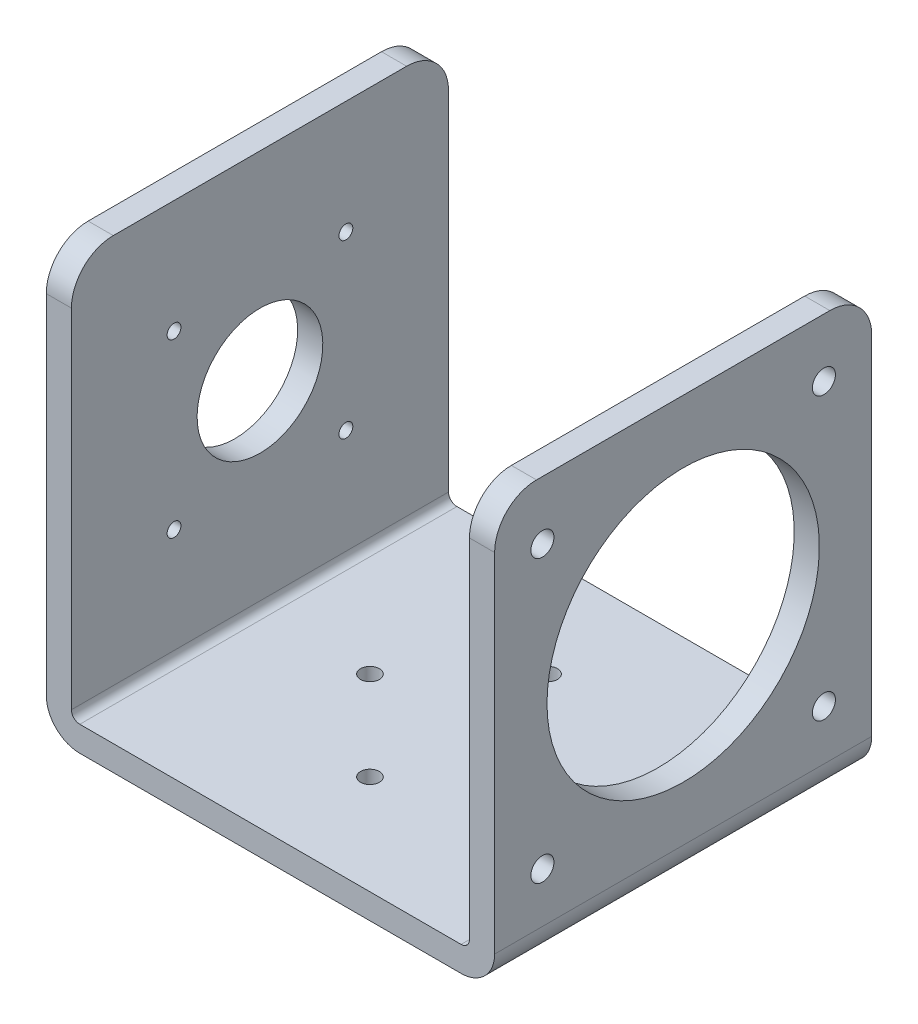
SolidWorks part; units mm, degrees
ref_plane "Płaszczyzna przednia" through (0, 0, 0) normal (0, 0, 1) x (1, 0, 0)
ref_plane "Płaszczyzna górna" through (0, 0, 0) normal (0, 1, 0) x (1, 0, 0)
ref_plane "Płaszczyzna prawa" through (0, 0, 0) normal (1, 0, 0) x (0, 0, -1)
sketch "Sketch1" plane through (0, 0, 0) normal (0, 0, 1) x (1, 0, 0)
  line L0 (-53.5, 0) -> (53.5, 0)
  line L1 (53.5, 0) -> (53.5, 101)
  line L2 (53.5, 101) -> (47.5, 101)
  line L3 (47.5, 101) -> (47.5, 6)
  line L4 (47.5, 6) -> (-47.5, 6)
  line L5 (-47.5, 6) -> (-47.5, 101)
  line L6 (-47.5, 101) -> (-53.5, 101)
  line L7 (-53.5, 101) -> (-53.5, 0)
  line L8 (0, 0) -> (0, 6) construction
  point P4 (0, 0)
  dimension "D1" = 6
  dimension "D2" = 107
  dimension "D3" = 101
  dimension "D4" = 101
extrude "Boss-Extrude1" add sketch "Sketch1" along normal blind 90
hole_wizard "M4 Clearance Hole1" positions "Sketch2" profile "Sketch3" hole size "M4" standard "DIN" end condition through all
sketch "Sketch2" plane through (0, 6, 0) normal (0, 1, 0) x (1, 0, 0)
  line L1 (-47.5, -90) -> (47.5, -90)
  line L2 (-47.5, -90) -> (-47.5, 0)
  line L3 (-47.5, 0) -> (47.5, 0)
  line L4 (47.5, -90) -> (47.5, 0)
  line L5 (-47.5, -90) -> (47.5, 0) construction
  line L6 (-47.5, 0) -> (47.5, -90) construction
  circle A0 centre (0, -45) radius 21.25
  point P77 (0, -23.75)
  point P79 (21.25, -45)
  point P81 (0, -66.25)
  point P83 (-21.25, -45)
  dimension "D1" = 42.5
sketch "Sketch3" plane through (-21.25, 6, 45) normal (1, 0, 0) x (0, 0, 1)
  line L0 (0, 0) -> (0, 6)
  line L1 (0, 6) -> (2.25, 6)
  line L2 (2.25, 6) -> (2.25, 0)
  line L5 (2.25, 0) -> (0, 0)
  line L11 (0, -6.35) -> (0, 107.95) construction
  dimension "Thru Hole Dia." = 4.5
  dimension "Thru Hole Depth" = 6
sketch "Sketch4" plane through (47.5, 0, 0) normal (-1, 0, 0) x (0, 0, 1)
  line L1 (0, 6) -> (90, 6) construction
  line L2 (0, 6) -> (0, 101) construction
  line L3 (0, 101) -> (90, 101) construction
  line L12 (90, 6) -> (90, 101) construction
  line L13 (0, 6) -> (90, 101) construction
  line L14 (0, 101) -> (90, 6) construction
  circle A0 centre (45, 53.5) radius 32.5
  point P0 (45, 53.5)
  dimension "D1" = 65
extrude "Cut-Extrude1" cut sketch "Sketch4" against normal through all
hole_wizard "M5 Clearance Hole1" positions "Sketch5" profile "Sketch6" hole size "M5" standard "DIN"
sketch "Sketch5" plane through (53.5, 0, 0) normal (1, 0, 0) x (0, 0, -1)
  line L0 (-45, 53.5) -> (-11.4124, 87.0876) construction
  circle A0 centre (-45, 53.5) radius 47.5 construction
  point P7 (-11.4124, 87.0876)
  point P17 (-11.4124, 19.9124)
  point P18 (-78.5876, 19.9124)
  point P19 (-78.5876, 87.0876)
  dimension "D1" = 95
  dimension "D2" = 4
sketch "Sketch6" plane through (53.5, 87.0876, 78.5876) normal (0, 1, 0) x (0, 0, -1)
  line L0 (0, 0) -> (0, 6)
  line L1 (0, 6) -> (2.75, 6)
  line L2 (2.75, 6) -> (2.75, 0)
  line L5 (2.75, 0) -> (0, 0)
  line L11 (0, -6.35) -> (0, 107.95) construction
  dimension "Thru Hole Dia." = 5.5
  dimension "Thru Hole Depth" = 6
sketch "Sketch7" plane through (-53.5, 0, 0) normal (-1, 0, 0) x (0, 0, 1)
  circle A0 centre (45, 53.5) radius 32.5 construction
  circle A1 centre (45, 53.5) radius 32.5 construction
  circle A2 centre (45, 53.5) radius 15
  dimension "D1" = 30
extrude "Cut-Extrude2" cut sketch "Sketch7" against normal up to next
fillet "Fillet1" radius 8 2 edges at (53.5, 0, 45) (-53.5, 0, 45)
fillet "Fillet2" radius 2 2 edges at (47.5, 6, 45) (-47.5, 6, 45)
fillet "Fillet3" radius 10 4 edges at (-50.5, 101, 90) (50.5, 101, 0) (-50.5, 101, 0) (50.5, 101, 90)
hole_wizard "Tap Drill for M4 Tap1" positions "Sketch8" profile "Sketch9" hole size "M4" standard "DIN" end condition up to next
sketch "Sketch8" plane through (-47.5, 0, 0) normal (1, 0, 0) x (0, 0, -1)
  line L0 (-45, 53.5) -> (-24.4939, 74.0061) construction
  circle A0 centre (-45, 53.5) radius 29 construction
  point P7 (-24.4939, 74.0061)
  point P17 (-24.4939, 32.9939)
  point P18 (-65.5061, 32.9939)
  point P19 (-65.5061, 74.0061)
  dimension "D1" = 58
  dimension "D2" = 4
sketch "Sketch9" plane through (-47.5, 74.0061, 65.5061) normal (0, 1, 0) x (0, 0, -1)
  line L0 (0, 0) -> (0, 6)
  line L1 (0, 6) -> (1.65, 6)
  line L2 (1.65, 6) -> (1.65, 0)
  line L5 (1.65, 0) -> (0, 0)
  line L11 (0, -6.35) -> (0, 107.95) construction
  dimension "Thru Hole Dia." = 3.3
  dimension "Thru Hole Depth" = 6
